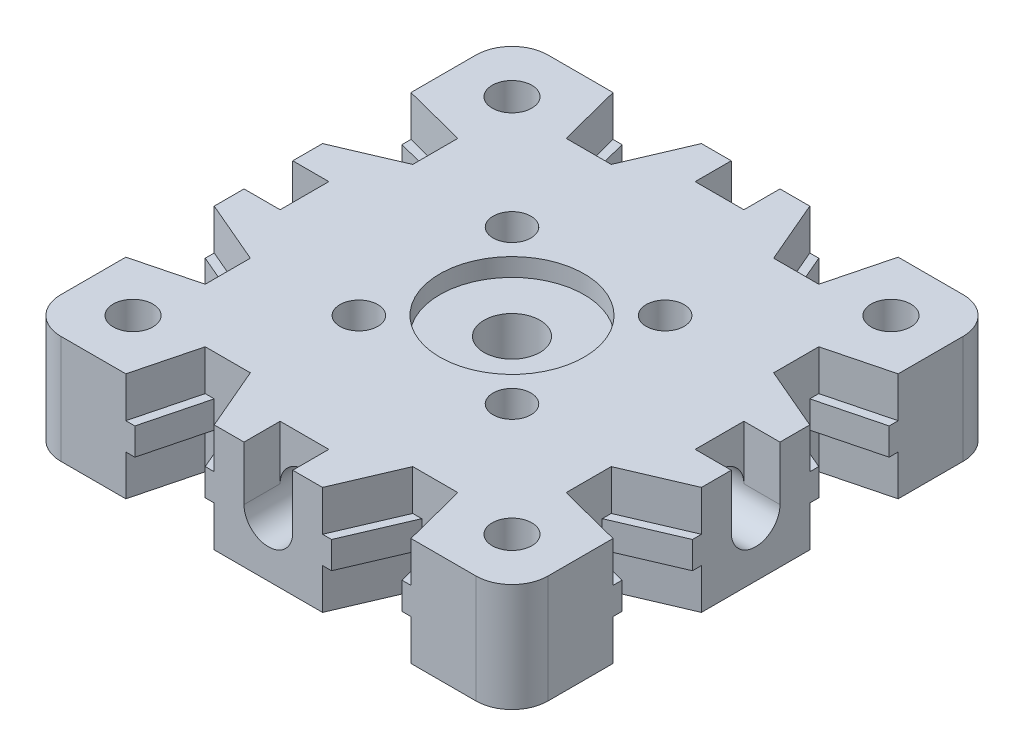
SolidWorks part; units mm, degrees
material "ABS"
ref_plane "正面" through (0, 0, 0) normal (0, 0, 1) x (1, 0, 0)
ref_plane "平面" through (0, 0, 0) normal (0, 1, 0) x (1, 0, 0)
ref_plane "右側面" through (0, 0, 0) normal (1, 0, 0) x (0, 0, -1)
sketch "ｽｹｯﾁ3" plane through (0, 0, 0) normal (0, 1, 0) x (1, 0, 0)
  line L1 (-13.5, 13.5) -> (13.5, 13.5)
  line L2 (-13.5, 13.5) -> (-13.5, -13.5)
  line L3 (-13.5, -13.5) -> (13.5, -13.5)
  line L4 (13.5, 13.5) -> (13.5, -13.5)
  line L5 (-13.5, 13.5) -> (13.5, -13.5) construction
  line L6 (-13.5, -13.5) -> (13.5, 13.5) construction
  point P0 (0, 0)
  dimension "D1" = 27
extrude "ﾎﾞｽ - 押し出し1" add sketch "ｽｹｯﾁ3" along normal mid plane 6
fillet "ﾌｨﾚｯﾄ1" radius 2 4 edges at (-13.5, 0, -13.5) (13.5, 0, -13.5) (-13.5, 0, 13.5) (13.5, 0, 13.5)
sketch "ｽｹｯﾁ4" plane through (0, 3, 0) normal (0, 1, 0) x (1, 0, 0)
  line L1 (-10.5, 10.5) -> (10.5, 10.5) construction
  line L2 (-10.5, 10.5) -> (-10.5, -10.5) construction
  line L3 (-10.5, -10.5) -> (10.5, -10.5) construction
  line L4 (10.5, 10.5) -> (10.5, -10.5) construction
  line L5 (-10.5, 10.5) -> (10.5, -10.5) construction
  line L6 (-10.5, -10.5) -> (10.5, 10.5) construction
  circle A0 centre (-10.5, 10.5) radius 1.1
  circle A1 centre (10.5, 10.5) radius 1.1
  circle A2 centre (-10.5, -10.5) radius 1.1
  circle A3 centre (10.5, -10.5) radius 1.1
  point P0 (0, 0)
  dimension "D6" = 2.2
  dimension "D1" = 21
  dimension "D2" = 21
extrude "ｶｯﾄ - 押し出し1" cut sketch "ｽｹｯﾁ4" against normal blind 6
sketch "ｽｹｯﾁ5" plane through (0, 3, 0) normal (0, 1, 0) x (1, 0, 0)
  circle A0 centre (0, 0) radius 1.55
  dimension "D1" = 3.1
extrude "ｶｯﾄ - 押し出し2" cut sketch "ｽｹｯﾁ5" against normal blind 6
sketch "ｽｹｯﾁ6" plane through (0, 3, 0) normal (0, 1, 0) x (1, 0, 0)
  line L0 (4.2426, 4.2426) -> (0, 0)
  line L1 (0, 0) -> (3.3762, 0)
  circle A0 centre (4.2426, 4.2426) radius 1.05
  dimension "D1" = 2.1
  dimension "D2" = 45
  dimension "D3" = 6
extrude "ｶｯﾄ - 押し出し3" cut sketch "ｽｹｯﾁ6" against normal blind 6
pattern_circular "円形ﾊﾟﾀｰﾝ1" count 4 over 360 about axis through (0, 0, 0) along (0, 1, 0) of "ｶｯﾄ - 押し出し3"
sketch "ｽｹｯﾁ7" plane through (0, 3, 0) normal (0, 1, 0) x (1, 0, 0)
  circle A0 centre (0, 0) radius 4
  dimension "D1" = 8
extrude "ｶｯﾄ - 押し出し4" cut sketch "ｽｹｯﾁ7" against normal blind 1
sketch "ｽｹｯﾁ11" plane through (0, 3, 0) normal (0, 1, 0) x (1, 0, 0)
  line L0 (3, 13.5) -> (4.5, 10)
  line L1 (11.5, 13.5) -> (-11.5, 13.5) construction
  line L2 (4.5, 10) -> (7, 10)
  line L3 (7, 10) -> (7.9, 13.5)
  dimension "D1" = 3.5
  dimension "D2" = 2.5
  dimension "D3" = 7
  dimension "D4" = 3
  dimension "D5" = 7.9
extrude "ｶｯﾄ - 押し出し8" cut sketch "ｽｹｯﾁ11" against normal through all and the other way through all
mirror "ﾐﾗｰ1" about plane through (0, 0, 0) normal (1, 0, 0) of "ｶｯﾄ - 押し出し8"
pattern_circular "円形ﾊﾟﾀｰﾝ2" count 4 over 360 about axis through (0, 0, 0) along (0, 1, 0) of "ｶｯﾄ - 押し出し8", "ﾐﾗｰ1"
sketch "ｽｹｯﾁ12" plane through (0, 0, 13.5) normal (0, 0, 1) x (1, 0, 0)
  circle A0 centre (0, 0) radius 1.35
  dimension "D1" = 2.7
extrude "ｶｯﾄ - 押し出し9" cut sketch "ｽｹｯﾁ12" against normal blind 8
pattern_circular "円形ﾊﾟﾀｰﾝ3" count 4 over 360 about axis through (0, 0, 0) along (0, 1, 0) of "ｶｯﾄ - 押し出し9"
sketch "ｽｹｯﾁ13" plane through (0, 0, 0) normal (0, 1, 0) x (1, 0, 0)
  line L0 (7.9, 13.5) -> (7, 10)
  line L1 (7, 10) -> (6.5, 10)
  line L2 (7, 10) -> (4.5, 10) construction
  line L3 (6.5, 10) -> (7.4, 13.5)
  line L4 (7.4, 13.5) -> (7.9, 13.5)
  line L5 (3, 13.5) -> (3.5, 13.5)
  line L6 (3.5, 13.5) -> (5, 10)
  line L7 (5, 10) -> (4.5, 10)
  line L8 (4.5, 10) -> (3, 13.5)
  dimension "D1" = 0.5
  dimension "D2" = 0.5
extrude "ﾎﾞｽ - 押し出し2" add sketch "ｽｹｯﾁ13" along normal mid plane 1.5
mirror "ﾐﾗｰ2" about plane through (0, 0, 0) normal (1, 0, 0) of "ﾎﾞｽ - 押し出し2"
pattern_circular "円形ﾊﾟﾀｰﾝ4" count 4 over 360 about axis through (0, 0, 0) along (0, 1, 0) of "ﾎﾞｽ - 押し出し2", "ﾐﾗｰ2"
ref_plane "平面1" through (0, 0, -10.5) normal (0, 0, -1) x (-1, 0, 0)
sketch "ｽｹｯﾁ18" plane through (0, 3, 0) normal (0, 1, 0) x (1, 0, 0)
  line L0 (0, 0) -> (6, 0)
  line L1 (0, 0) -> (0, 6)
  dimension "D1" = 6
sketch "ｽｹｯﾁ19" plane through (0, 0, 0) normal (0, 0, 1) x (1, 0, 0)
  line L0 (0, 3) -> (0, 9)
  line L1 (0, 3) -> (6, 3) construction
sketch "ｽｹｯﾁ22" plane through (0, 0, 13.5) normal (0, 0, 1) x (1, 0, 0)
  line L0 (0, 3) -> (6, 3) construction
  line L1 (-1.35, 0) -> (1.35, 0)
  line L2 (-1.35, 0) -> (-1.35, 3)
  line L3 (-1.35, 3) -> (1.35, 3)
  line L4 (1.35, 0) -> (1.35, 3)
  line L5 (-1.35, 0) -> (1.35, 3) construction
  line L6 (-1.35, 3) -> (1.35, 0) construction
  circle A0 centre (0, 0) radius 1.35 construction
  circle A1 centre (0, 0) radius 1.35 construction
  point P4 (0, 1.5)
extrude "ｶｯﾄ - 押し出し15" cut sketch "ｽｹｯﾁ22" against normal blind 2
pattern_circular "円形ﾊﾟﾀｰﾝ11" count 4 over 360 about axis through (0, 0, 0) along (0, 1, 0) of "ｶｯﾄ - 押し出し15"
sketch "ｽｹｯﾁ27" plane through (0, -3, 0) normal (0, -1, 0) x (1, 0, 0)
  line L0 (0, -6) -> (0, 0)
  line L1 (0, 0) -> (-6, 0)
